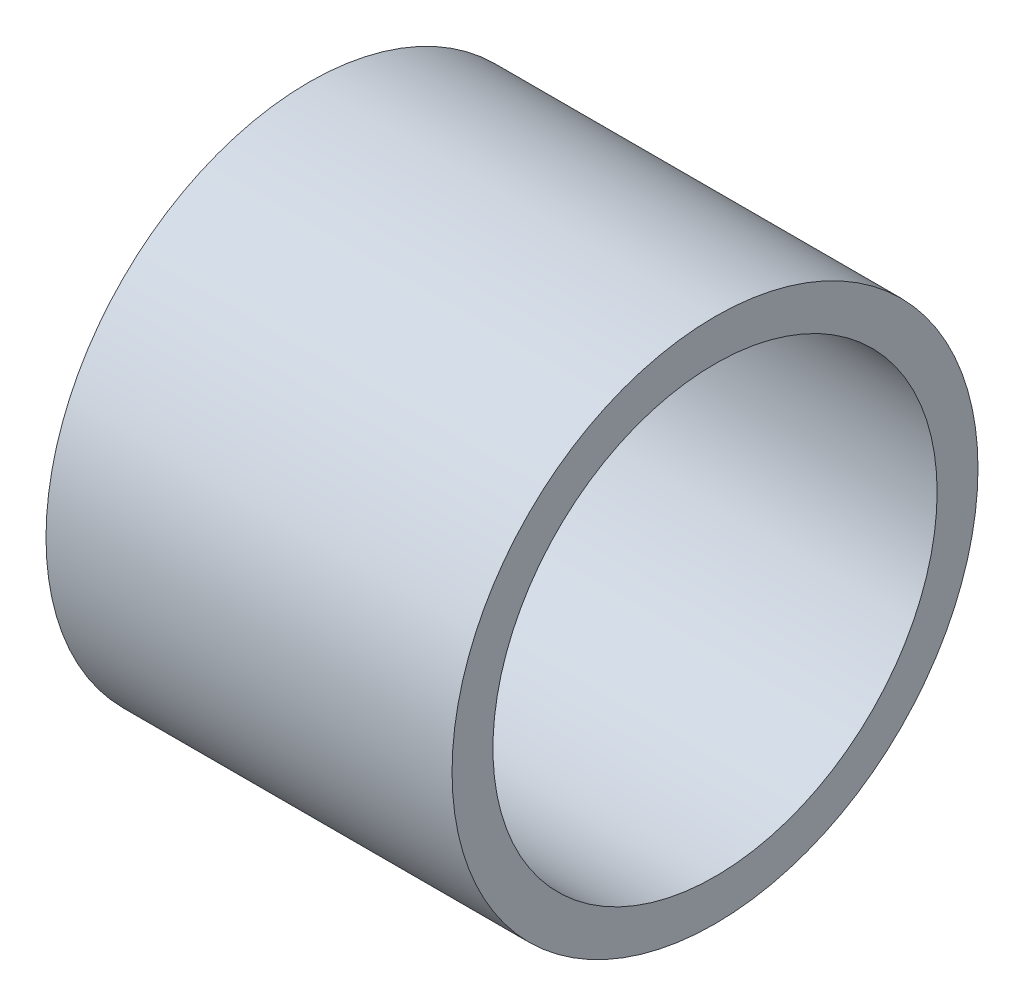
SolidWorks part; units mm, degrees
ref_plane "Alzado" through (0, 0, 0) normal (0, 0, 1) x (1, 0, 0)
ref_plane "Planta" through (0, 0, 0) normal (0, 1, 0) x (1, 0, 0)
ref_plane "Vista lateral" through (0, 0, 0) normal (1, 0, 0) x (0, 0, -1)
sketch "Croquis1" plane through (0, 0, 0) normal (1, 0, 0) x (0, 0, -1)
  circle A0 centre (0, 0) radius 9.65
  circle A1 centre (0, 0) radius 8.15
  dimension "D1" = 19.3
  dimension "D2" = 1.5
extrude "Saliente-Extruir1" add sketch "Croquis1" against normal blind 14.9
